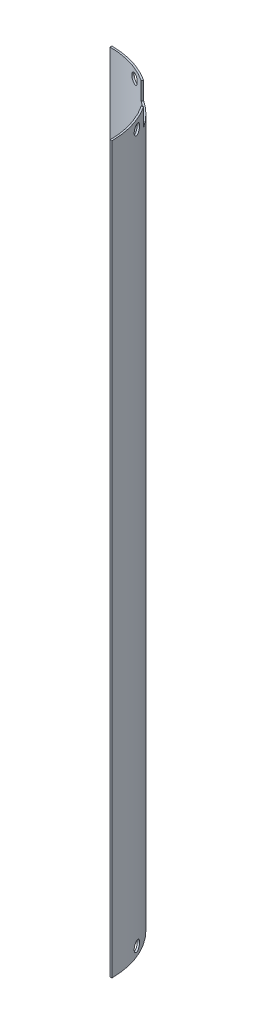
SolidWorks part; units mm, degrees
material "1060 Alloy"
ref_plane "Front Plane" through (0, 0, 0) normal (0, 0, 1) x (1, 0, 0)
ref_plane "Top Plane" through (0, 0, 0) normal (0, 1, 0) x (1, 0, 0)
ref_plane "Right Plane" through (0, 0, 0) normal (1, 0, 0) x (0, 0, -1)
sketch "Sketch1" plane through (0, 0, 0) normal (0, 1, 0) x (1, 0, 0)
  line L0 (0, 0) -> (0, 92)
  line L1 (0, 0) -> (92, 0)
  circle A0 centre (0, 0) radius 90
  circle A1 centre (0, 0) radius 92
  dimension "Internal Diameter" = 180
  dimension "External Diameter" = 184
extrude "Boss-Extrude1" add sketch "Sketch1" along normal blind 812 contours L1 A1 L0 A0
ref_plane "Plane1" through (0, 10, 0) normal (0, -1, 0) x (-1, 0, 0)
sketch "Sketch2" plane through (0, 10, 0) normal (0, -1, 0) x (-1, 0, 0)
  line L0 (0, 0) -> (-84.9969, 35.2069)
  line L1 (0, 0) -> (-65.0538, 65.0538)
  line L2 (0, 0) -> (-92, 0) construction
  line L3 (0, 0) -> (-35.2069, 84.9969)
  arc A0 (0, 92) -> (-92, 0) centre (0, 0) ccw construction
  dimension "D1" = 135
  dimension "D2" = 22.5
ref_plane "Plane2" through (84.9969, 0, -35.2069) normal (0.9239, 0, -0.3827) x (-0.3827, 0, -0.9239)
ref_plane "Plane3" through (35.2069, 0, -84.9969) normal (0.3827, 0, -0.9239) x (-0.9239, 0, -0.3827)
sketch "Sketch3" plane through (84.9969, 0, -35.2069) normal (0.9239, 0, -0.3827) x (-0.3827, 0, -0.9239)
  circle A0 centre (0, 10) radius 5.565
  point P0 (0, 10)
  dimension "Right Hole Diameter" = 11.13
sketch "Sketch5" plane through (35.2069, 0, -84.9969) normal (0.3827, 0, -0.9239) x (-0.9239, 0, -0.3827)
  line L0 (0, 10) -> (-84.9969, 10) construction
  circle A0 centre (0, 10) radius 5.565
  dimension "Left Hole Diameter" = 11.13
ref_plane "Plane4" through (65.0538, 0, -65.0538) normal (0.7071, 0, -0.7071) x (-0.7071, 0, -0.7071)
sketch "Sketch6" plane through (65.0538, 0, -65.0538) normal (0.7071, 0, -0.7071) x (-0.7071, 0, -0.7071)
  line L0 (0, 10) -> (-65.0538, 10) construction
  line L1 (0, 10) -> (35.2069, 10) construction
  circle A0 centre (0, 10) radius 2.5
  dimension "Middle Hole Diameter" = 5
extrude "Cut-Extrude2" cut sketch "Sketch3" against normal up to surface (2.1722 mm away) contours A0
extrude "Cut-Extrude3" cut sketch "Sketch5" against normal up to surface (2.1722 mm away) contours A0
pattern_linear "LPattern2" count 2 spacing 792 along (0, 1, 0) of "Cut-Extrude2", "Cut-Extrude3"
sketch "Sketch7" plane through (0, 0, 0) normal (0, -1, 0) x (1, 0, 0)
  line L0 (0, 0) -> (65.0538, -65.0538) construction
  line L1 (0.3118, -0.3118) -> (57.9282, -0.3118) construction
  line L2 (0.3118, -0.3118) -> (76.4474, -51.184)
  line L3 (0.3118, -0.3118) -> (51.184, -76.4474)
  line L6 (92, 0) -> (90, 0)
  line L7 (0, -90) -> (0, -92)
  line L8 (92, 0) -> (90, 0)
  line L11 (0, -90) -> (0, -92)
  arc A0 (0, -92) -> (92, 0) centre (0, 0) ccw construction
  arc A2 (0, -90) -> (90, 0) centre (0, 0) ccw
  arc A3 (0, -92) -> (92, 0) centre (0, 0) ccw
  arc A4 (0, -90) -> (90, 0) centre (0, 0) ccw
  arc A8 (0, -92) -> (92, 0) centre (0, 0) ccw
  arc M5 (90, 0) -> (0, -90) centre (0, 0) cw
  arc M7 (0, -92) -> (92, 0) centre (0, 0) ccw
  dimension "D1" = 45
  dimension "D2" = 11.25
  dimension "D3" = 0
extrude "Cut-Extrude5" cut sketch "Sketch7" against normal blind 20 contours L3 L2 M5 M7
move or copy body "Body-Move/Copy1" bodies to move or copy 107 copy no rotation origin (0, 252, 0) rotation axis (0.7071, 0, -0.7071) rotation angle 180
equation "\"Total Panel Length\"= 812"
equation "\"Internal Panel Diameter\"= 180"
equation "\"External Panel Diameter\"= 184"
equation "\"L & R Mounting Hole Diameter\"= 11.13"
equation "\"M Mounting Hole DIameter\"= 5"
equation "\"Mounting Hole Dist. from Top\"= 10"
equation "\"Mounting Hole Dist. from Base\"= 10"
equation "\"External Diameter@Sketch1\"= \"External Panel Diameter\""
equation "\"Internal Diameter@Sketch1\"= \"Internal Panel Diameter\""
equation "\"Panel Length@Boss-Extrude1\"= \"Total Panel Length\""
equation "\"Right Hole Diameter@Sketch3\"= \"L & R Mounting Hole Diameter\""
equation "\"Left Hole Diameter@Sketch5\"= \"L & R Mounting Hole Diameter\""
equation "\"Middle Hole Diameter@Sketch6\" = \"M Mounting Hole DIameter\""
equation "\"Mounting from Top@Plane1\"= \"Mounting Hole Dist. from Top\""
equation "\"Mounting from Base@LPattern2\"= \"Total Panel Length\" - \"Mounting Hole Dist. from Base\" - \"Mounting Hole Dist. from Top\""
equation "\"Top Tab Length@Cut-Extrude5\" = \"Top Tab Length\""
equation "\"Top Tab Length\"= 20"
